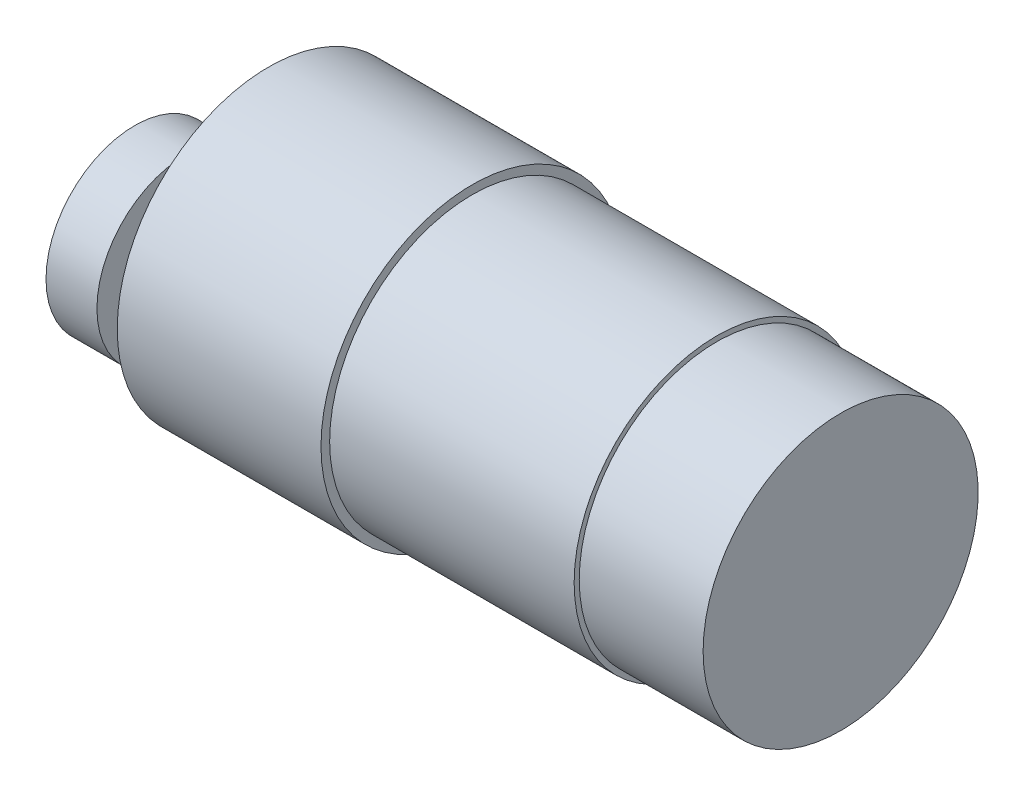
SolidWorks part; units mm, degrees
ref_plane "Face" through (0, 0, 0) normal (0, 0, 1) x (1, 0, 0)
ref_plane "Dessus" through (0, 0, 0) normal (0, 1, 0) x (1, 0, 0)
ref_plane "Droite" through (0, 0, 0) normal (1, 0, 0) x (0, 0, -1)
sketch "Esquisse6" plane through (0, 0, 0) normal (1, 0, 0) x (0, 0, -1)
  circle A0 centre (0, 0) radius 18.8595
  dimension "D1" = 37.719
extrude "Boss.-Extru.2" add sketch "Esquisse6" along normal blind 25.4
sketch "Esquisse7" plane through (25.4, 0, 0) normal (1, 0, 0) x (0, 0, -1)
  circle A0 centre (0, 0) radius 17.78
  dimension "D1" = 35.56
extrude "Boss.-Extru.3" add sketch "Esquisse7" along normal blind 30.48
sketch "Esquisse8" plane through (55.88, 0, 0) normal (1, 0, 0) x (0, 0, -1)
  circle A0 centre (0, 0) radius 17.145
  dimension "D1" = 34.29
extrude "Boss.-Extru.4" add sketch "Esquisse8" along normal blind 15.4432
sketch "Esquisse9" plane through (0, 0, 0) normal (-1, 0, 0) x (0, 0, 1)
  circle A0 centre (0, -6.858) radius 5.969
  dimension "D1" = 11.938
  dimension "D2" = 6.858
extrude "Boss.-Extru.5" add sketch "Esquisse9" along normal blind 6.096
sketch "Esquisse10" plane through (-6.096, 0, 0) normal (-1, 0, 0) x (0, 0, 1)
  circle A0 centre (0, -6.858) radius 4.699
  circle A1 centre (0, -6.858) radius 5.969 construction
  dimension "D1" = 9.398
extrude "Boss.-Extru.6" add sketch "Esquisse10" along normal blind 4.2333
sketch "Esquisse11" plane through (-10.3293, 0, 0) normal (-1, 0, 0) x (0, 0, 1)
  circle A0 centre (0, -6.858) radius 11.0617
  circle A1 centre (0, -6.858) radius 4.699 construction
  dimension "D1" = 22.1234
extrude "Boss.-Extru.7" add sketch "Esquisse11" along normal blind 6.35
sketch "Esquisse12" plane through (-16.6793, 0, 0) normal (-1, 0, 0) x (0, 0, 1)
  circle A0 centre (0, -6.858) radius 4.7752
  circle A1 centre (0, -6.858) radius 11.0617 construction
  dimension "D1" = 9.5504
extrude "Boss.-Extru.8" add sketch "Esquisse12" along normal blind 3.302
hole_wizard "Perçage pour tuyau pour trou taraudé 1/161" positions "Esquisse13" profile "Esquisse15" hole size "1/16" standard "Ansi Inch"
sketch "Esquisse13" plane through (-19.9813, 0, 0) normal (-1, 0, 0) x (0, 0, 1)
  circle A1 centre (0, -6.858) radius 4.7752 construction
  point P0 (0, -6.858)
sketch "Esquisse15" plane through (-19.9813, -6.858, 0) normal (0, 1, 0) x (0, 0, 1)
  line L0 (0, 0) -> (0, 19.9813)
  line L1 (0, 19.9813) -> (3.0734, 19.9813)
  line L2 (3.0734, 19.9813) -> (3.0734, 0)
  line L5 (3.0734, 0) -> (0, 0)
  line L10 (0, 19.9813) -> (-3.0734, 19.9813) construction
  line L11 (0, -6.35) -> (0, 107.95) construction
  dimension "Diamètre du perçage" = 6.1468
  dimension "Profondeur du perçage" = 19.9813
  dimension "Angle de pointe" = 180
sketch "Esquisse16" plane through (0, 0, 0) normal (-1, 0, 0) x (0, 0, 1)
  line L0 (-1.778, -4.4768) -> (1.778, -4.4768)
  arc A0 (-1.778, -4.4768) -> (1.778, -4.4768) centre (0, -6.858) ccw
  point P5 (0, -4.4768)
  dimension "D1" = 5.9436
  dimension "D2" = 3.556
extrude "Boss.-Extru.9" add sketch "Esquisse16" along normal up to surface (19.9813 mm away) up to face at (-19.9813, -6.858, 3.0734)
sketch "Esquisse17" plane through (-19.9813, 0, 0) normal (-1, 0, 0) x (0, 0, 1)
  line L0 (-1.778, -4.4768) -> (1.778, -4.4768)
  arc A3 (-1.778, -4.4768) -> (1.778, -4.4768) centre (0, -6.858) ccw
extrude "Boss.-Extru.10" add sketch "Esquisse17" along normal blind 2.032
sketch "Esquisse18" plane through (-16.6793, 0, 0) normal (-1, 0, 0) x (0, 0, 1)
  circle A1 centre (0, -0.254) radius 1.4605
  circle A2 centre (0, -6.858) radius 4.7752 construction
  circle A3 centre (6.604, -6.858) radius 1.4605
  circle A4 centre (0, -13.462) radius 1.4605
  circle A5 centre (-6.604, -6.858) radius 1.4605
  point P15 (0, -6.858)
  dimension "D2" = 2.921
  dimension "D1" = 6.604
  dimension "D3" = 4
extrude "Enlèv. mat.-Extru.2" cut sketch "Esquisse18" against normal up to next
sketch "Esquisse19" plane through (0, 0, 0) normal (-1, 0, 0) x (0, 0, 1)
  circle A1 centre (7.2909, 15.3114) radius 1.5
  circle A2 centre (7.2533, -15.5106) radius 1.5
  circle A3 centre (-16.8094, 1.555) radius 1.5
  point P12 (0.1484, -0.0315)
  dimension "D1" = 3
  dimension "D3" = 27.75
  dimension "D2" = 3
  dimension "D4" = 3
  dimension "D5" = 29.5
extrude "Enlèv. mat.-Extru.3" cut sketch "Esquisse19" against normal blind 5
